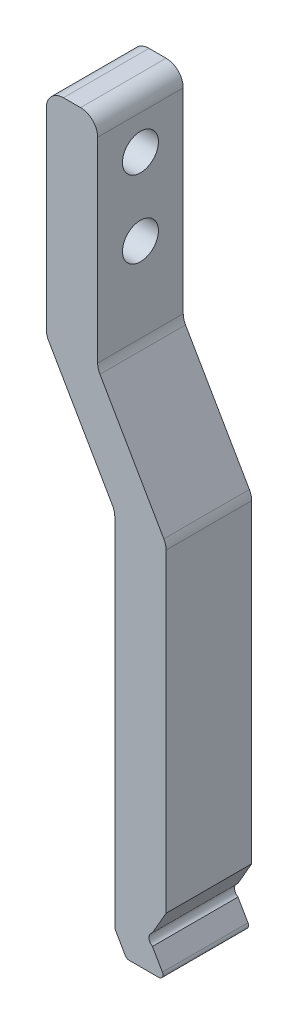
SolidWorks part; units mm, degrees
ref_plane "前视基准面" through (0, 0, 0) normal (0, 0, 1) x (1, 0, 0)
ref_plane "上视基准面" through (0, 0, 0) normal (0, 1, 0) x (1, 0, 0)
ref_plane "右视基准面" through (0, 0, 0) normal (1, 0, 0) x (0, 0, -1)
sketch "草图1" plane through (0, 0, 0) normal (0, 0, 1) x (1, 0, 0)
  line L0 (-9, 3.4641) -> (-11, 0)
  line L1 (5.5, 9.5263) -> (-5.5, 9.5263) construction
  line L2 (-5.5, 9.5263) -> (-11, 0) construction
  line L3 (-11, 0) -> (-5.5, -9.5263) construction
  line L4 (-5.5, -9.5263) -> (5.5, -9.5263) construction
  line L5 (5.5, -9.5263) -> (11, 0) construction
  line L6 (11, 0) -> (5.5, 9.5263) construction
  line L7 (-11, 0) -> (-9, -3.4641)
  line L9 (-17, 80) -> (-23, 80)
  line L11 (-15, -3.4641) -> (-9, -3.4641)
  line L12 (-23, 80) -> (-23, 55)
  line L13 (-23, 55) -> (-15, 41.1436)
  line L14 (-15, 41.1436) -> (-15, -3.4641)
  line L15 (0, 0) -> (0, 69.5816) construction
  line L16 (-17, 80) -> (-17, 54.6077)
  line L17 (-17, 54.6077) -> (-9, 40.7513)
  line L18 (-9, 40.7513) -> (-9, 3.4641)
  circle A0 centre (0, 0) radius 9.5263 construction
  dimension "D1" = 11
  dimension "D2" = 4
  dimension "D3" = 25
  dimension "D4" = 5
  dimension "D5" = 34
  dimension "D6" = 80
  dimension "D8" = 6
  dimension "D9" = 4
extrude "凸台-拉伸1" add sketch "草图1" along normal blind 10
sketch "草图2" plane through (-17, 0, 0) normal (1, 0, 0) x (0, 0, -1)
  line L0 (-5, 80) -> (-5, 65) construction
  line L1 (-10, 80) -> (0, 80) construction
  circle A0 centre (-5, 65) radius 2.1
  circle A1 centre (-5, 74) radius 2.1
  dimension "D1" = 4.2
  dimension "D2" = 9
  dimension "D3" = 6
extrude "切除-拉伸1" cut sketch "草图2" against normal through all
sketch "草图3" plane through (0, 0, 10) normal (0, 0, 1) x (1, 0, 0)
  line L0 (-10.2, 0) -> (-11, 0) construction
  line L1 (-15, -1.0718) -> (-13.6188, -3.4641)
  line L2 (-15, 41.1436) -> (-15, -3.4641) construction
  line L3 (-15, -3.4641) -> (-9, -3.4641) construction
  line L4 (-9, -3.4641) -> (-11, 0) construction
  line L5 (-15, -1.0718) -> (-15, -3.4641)
  line L6 (-15, -3.4641) -> (-13.6188, -3.4641)
  circle A0 centre (-10.2, 0) radius 0.8
  dimension "D1" = 1.6
  dimension "D2" = 4
extrude "切除-拉伸2" cut sketch "草图3" against normal through all
fillet "圆角1" radius 0.5 3 edges at (-9, -3.4641, 5) (-15, -1.0718, 5) (-13.6188, -3.4641, 5)
fillet "圆角2" radius 2 6 edges at (-15, 41.1436, 5) (-23, 55, 5) (-23, 80, 5) (-17, 54.6077, 5) (-9, 40.7513, 5) (-17, 80, 5)
